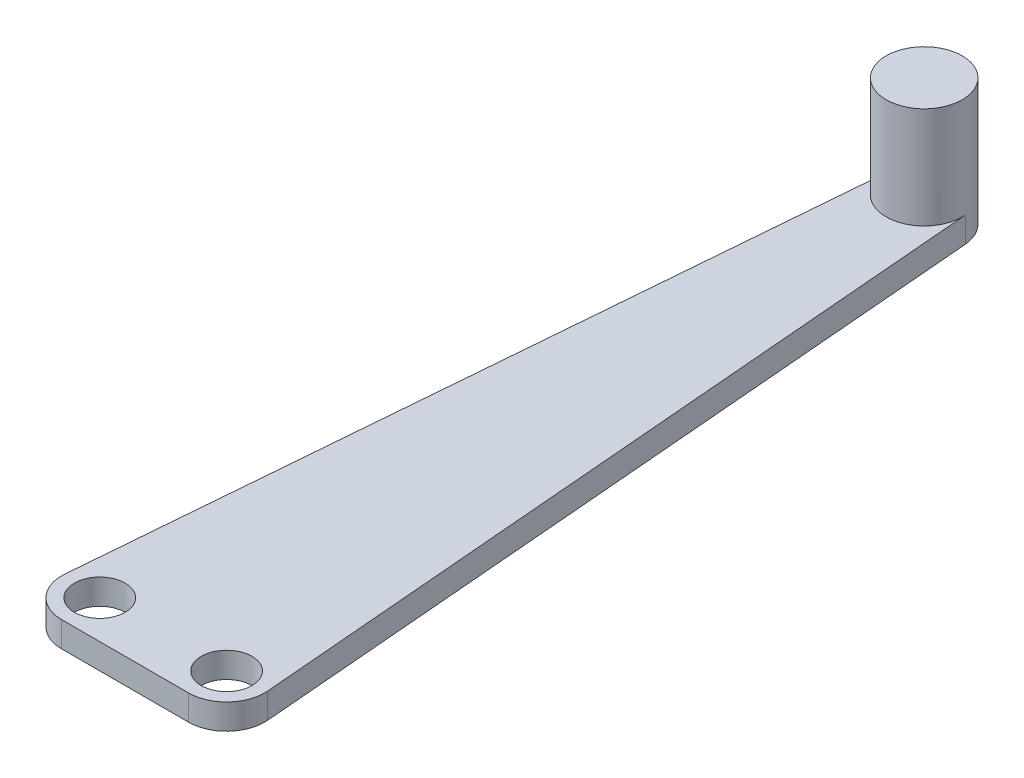
SolidWorks part; units mm, degrees
ref_plane "前基準面" through (0, 0, 0) normal (0, 0, 1) x (1, 0, 0)
ref_plane "上基準面" through (0, 0, 0) normal (0, 1, 0) x (1, 0, 0)
ref_plane "右基準面" through (0, 0, 0) normal (1, 0, 0) x (0, 0, -1)
sketch "草圖1" plane through (0, 0, 0) normal (0, 1, 0) x (1, 0, 0)
  line L0 (-25, 0) -> (25, 0) construction
  line L1 (0, 0) -> (0, -31.5853) construction
  line L2 (-25, -15) -> (25, -15)
  line L3 (-39.9482, 1.2457) -> (-14.9482, 301.2457)
  line L4 (14.9482, 301.2457) -> (39.9482, 1.2457)
  circle A1 centre (25, 0) radius 10
  circle A2 centre (25, 0) radius 15
  circle A3 centre (0, 300) radius 15
  circle A4 centre (0, 300) radius 10
  circle A5 centre (-25, 0) radius 15
  circle A6 centre (-25, 0) radius 10
  point P4 (0, 0)
  dimension "D2" = 20
  dimension "D3" = 30
  dimension "D4" = 20
  dimension "D5" = 30
  dimension "D1" = 50
  dimension "D6" = 300
extrude "填料-伸長1" add sketch "草圖1" along normal blind 10 contours L3 A5 L2 A2 L4 A3 | A5 A6 | A2 A1 | A3 A4
sketch "草圖2" plane through (0, 10, 0) normal (0, 1, 0) x (1, 0, 0)
  circle A0 centre (0, 300) radius 15
extrude "填料-伸長2" add sketch "草圖2" along normal blind 40
